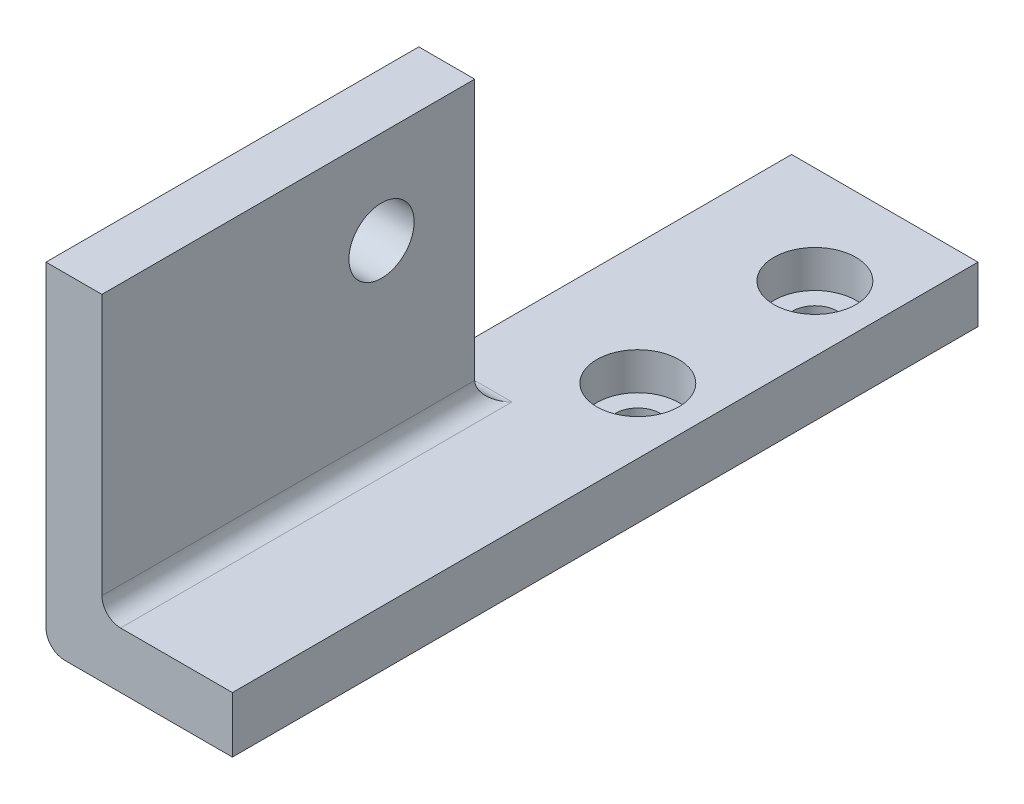
SolidWorks part; units mm, degrees
ref_plane "Front Plane" through (0, 0, 0) normal (0, 0, 1) x (1, 0, 0)
ref_plane "Top Plane" through (0, 0, 0) normal (0, 1, 0) x (1, 0, 0)
ref_plane "Right Plane" through (0, 0, 0) normal (1, 0, 0) x (0, 0, -1)
sketch "Sketch1" plane through (0, 0, 0) normal (0, 1, 0) x (1, 0, 0)
  line L0 (6.5, 5.25) -> (6.5, 14.75) construction
  line L1 (0, 0) -> (10, 0)
  line L2 (0, 0) -> (0, 20)
  line L3 (0, 20) -> (10, 20)
  line L4 (10, 0) -> (10, 20)
  circle A0 centre (6.5, 5.25) radius 1.175
  circle A1 centre (6.5, 14.75) radius 1.175
  point P9 (6.5, 10)
  point P10 (10, 10)
  dimension "D3" = 9.5
  dimension "D4" = 2.35
  dimension "D5" = 2.35
  dimension "D6" = 6.5
  dimension "D1" = 20
  dimension "D2" = 10
extrude "Boss-Extrude1" add sketch "Sketch1" along normal blind 3
sketch "Sketch2" plane through (0, 3, 0) normal (0, 1, 0) x (1, 0, 0)
  point P0 (6.5, 14.75)
  point P1 (6.5, 5.25)
hole_wizard "CBORE for M2 SHCS1" positions "Sketch2" profile "Sketch3" counterbore size "M2" standard "ANSI Metric" end condition through all
sketch "Sketch3" plane through (6.5, 3, -14.75) normal (1, 0, 0) x (0, 0, 1)
  line L0 (0, 0) -> (0, 3)
  line L1 (0, 3) -> (1.2, 3)
  line L3 (1.2, 3) -> (1.2, 2)
  line L4 (1.2, 2) -> (2.2, 2)
  line L5 (2.2, 2) -> (2.2, 0)
  line L7 (2.2, 0) -> (0, 0)
  line L11 (0, -6.35) -> (0, 107.95) construction
  dimension "Thru Hole Dia." = 2.4
  dimension "Thru Hole Depth" = 3
  dimension "C'Bore Dia." = 4.4
  dimension "C'Bore Depth" = 2
sketch "Sketch6" plane through (0, 0, 0) normal (0, 0, -1) x (-1, 0, 0)
  line L1 (0, 0) -> (-10, 0)
  line L2 (0, 0) -> (0, 3)
  line L3 (0, 3) -> (-10, 3)
  line L4 (-10, 0) -> (-10, 3)
  line L5 (-10, 3) -> (0, 3) construction
  line L6 (-10, 3) -> (-10, 0) construction
  dimension "D1" = 0
extrude "Boss-Extrude2" add sketch "Sketch6" against normal blind 20
sketch "Sketch8" plane through (0, 3, 0) normal (0, 1, 0) x (1, 0, 0)
  line L2 (0, -20) -> (3, -20)
  line L3 (0, -20) -> (0, 0)
  line L4 (0, 0) -> (3, 0)
  line L5 (3, -20) -> (3, 0)
  dimension "D1" = 3
  dimension "D2" = 20
extrude "Boss-Extrude3" add sketch "Sketch8" along normal blind 15
sketch "Sketch9" plane through (3, 0, 0) normal (1, 0, 0) x (0, 0, -1)
  line L1 (20, 3) -> (-20, 3) construction
  line L2 (-20, 18) -> (-20, 3) construction
  circle A0 centre (-5, 13) radius 1.75
  dimension "D1" = 10
  dimension "D2" = 15
  dimension "D3" = 3.5
extrude "Cut-Extrude1" cut sketch "Sketch9" against normal through all
fillet "Fillet1" radius 1 2 edges at (1.5, 3, 0) (3, 3, 10)
fillet "Fillet2" radius 1 1 edges at (0, 0, 0)
